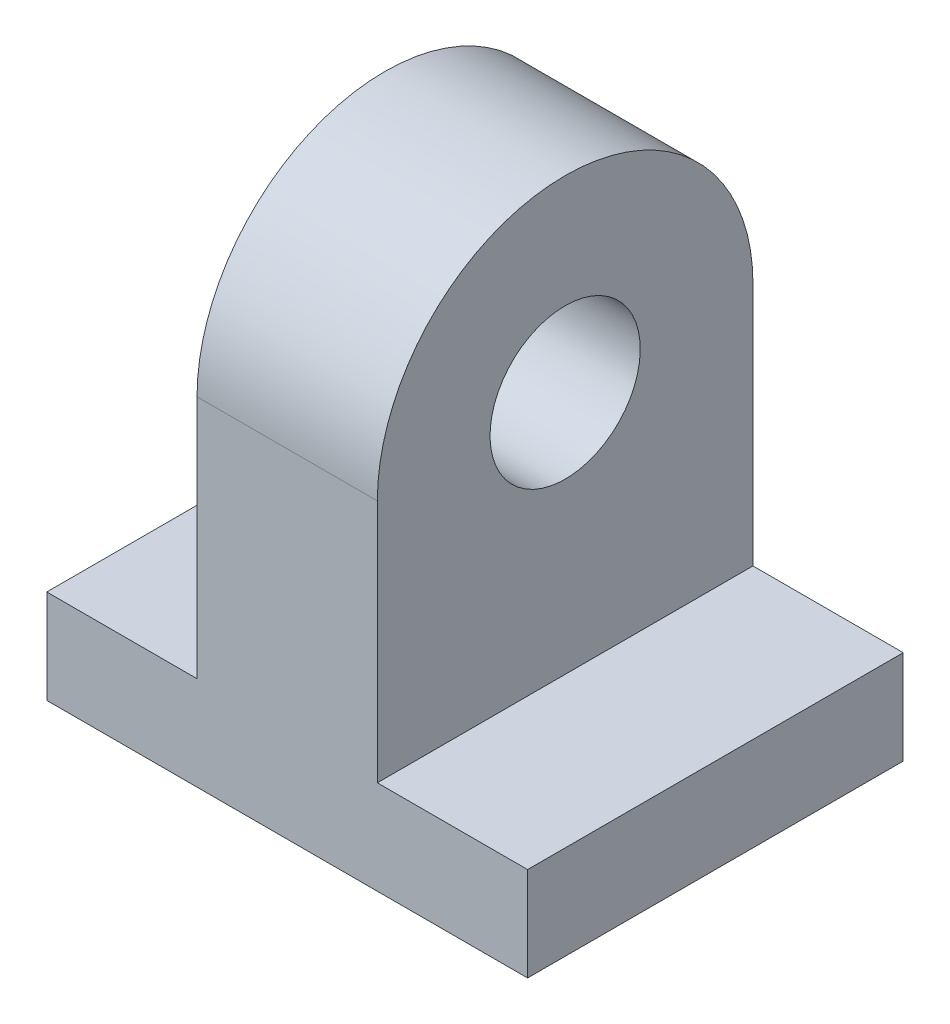
SolidWorks part; units mm, degrees
ref_plane "Спереди" through (0, 0, 0) normal (0, 0, 1) x (1, 0, 0)
ref_plane "Сверху" through (0, 0, 0) normal (0, 1, 0) x (1, 0, 0)
ref_plane "Справа" through (0, 0, 0) normal (1, 0, 0) x (0, 0, -1)
sketch "Эскиз1" plane through (0, 0, 0) normal (0, 0, 1) x (1, 0, 0)
  line L0 (-6.4, 0) -> (6.4, 0)
  line L1 (6.4, 0) -> (6.4, 2.5)
  line L2 (6.4, 2.5) -> (2.4, 2.5)
  line L3 (2.4, 2.5) -> (2.4, 14)
  line L4 (2.4, 14) -> (-2.4, 14)
  line L5 (-2.4, 14) -> (-2.4, 2.5)
  line L6 (-2.4, 2.5) -> (-6.4, 2.5)
  line L7 (-6.4, 2.5) -> (-6.4, 0)
  point P3 (0, 0)
  dimension "D1" = 4
  dimension "D2" = 4.8
  dimension "D3" = 2.5
  dimension "D4" = 14
extrude "Бобышка-Вытянуть1" add sketch "Эскиз1" along normal blind 10
sketch "Эскиз2" plane through (2.4, 0, 0) normal (1, 0, 0) x (0, 0, -1)
  line L0 (-5, 14) -> (-5, 2.7606) construction
  line L1 (-10, 14) -> (0, 14) construction
  line L2 (-10, 0) -> (0, 0) construction
  line L3 (-10, 9) -> (0, 9) construction
  line L4 (-10, 9) -> (-10, 0)
  line L5 (-10, 0) -> (0, 0)
  line L6 (0, 0) -> (0, 9)
  circle A0 centre (-5, 9) radius 2
  arc A1 (0, 9) -> (-10, 9) centre (-5, 9) ccw
  dimension "D1" = 4
  dimension "D2" = 9
extrude "Вырез-Вытянуть3" cut sketch "Эскиз2" against normal through all flip side to cut
